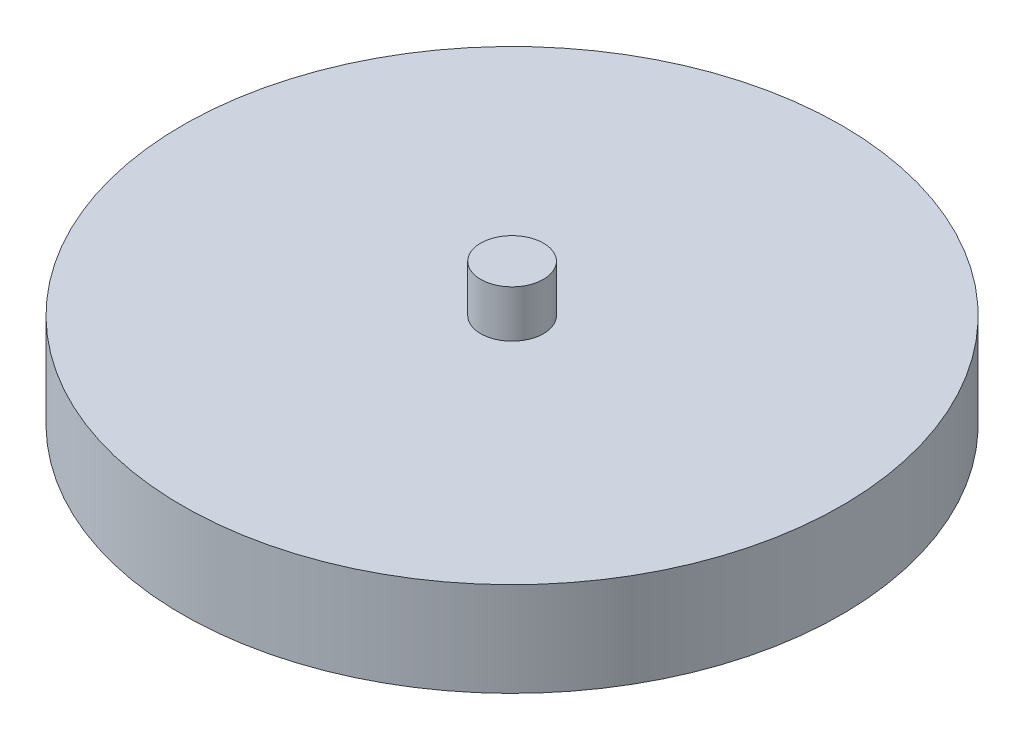
SolidWorks part; units mm, degrees
material "AISI 316 Stainless Steel Sheet (SS)"
ref_plane "Front Plane" through (0, 0, 0) normal (0, 0, 1) x (1, 0, 0)
ref_plane "Top Plane" through (0, 0, 0) normal (0, 1, 0) x (1, 0, 0)
ref_plane "Right Plane" through (0, 0, 0) normal (1, 0, 0) x (0, 0, -1)
sketch "Sketch1" plane through (0, 0, 0) normal (0, 0, 1) x (1, 0, 0)
  line L0 (0, 0) -> (0, 58.7368) construction
  line L3 (-10, 0) -> (-105, 0)
  line L4 (-105, 0) -> (-105, -30)
  line L5 (-105, -30) -> (0, -30)
  line L8 (-10, 0) -> (-10, 15)
  line L9 (-10, 15) -> (0, 15)
  line L10 (0, 15) -> (0, -30)
  point P3 (-0.9617, -20)
  dimension "D1" = 20
  dimension "D2" = 15
  dimension "D3" = 30
  dimension "D4" = 210
revolve "Revolve1" add sketch "Sketch1" angle 360 about L0
cosmetic thread "Cosmetic Thread1" parameters "D2"=17.252
